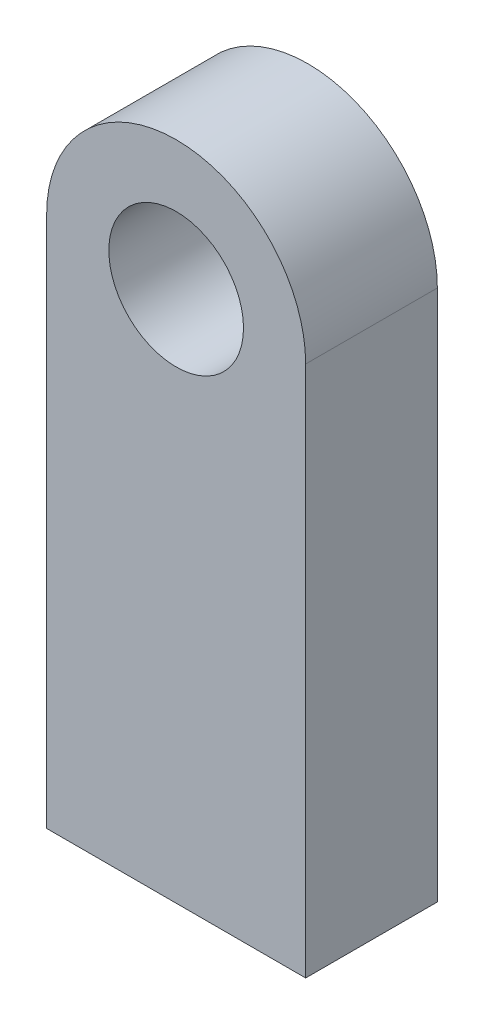
SolidWorks part; units mm, degrees
ref_plane "Front Plane" through (0, 0, 0) normal (0, 0, 1) x (1, 0, 0)
ref_plane "Top Plane" through (0, 0, 0) normal (0, 1, 0) x (1, 0, 0)
ref_plane "Right Plane" through (0, 0, 0) normal (1, 0, 0) x (0, 0, -1)
sketch "Sketch1" plane through (0, 0, 0) normal (0, 0, 1) x (1, 0, 0)
  line L0 (0, 0) -> (-19.6703, 0)
  line L1 (-19.6703, 0) -> (-19.6703, 40.3819)
  line L2 (0, 0) -> (0, 40.3819)
  arc A0 (-19.6703, 40.3819) -> (0, 40.3819) centre (-9.8351, 40.3819) cw
extrude "Boss-Extrude1" add sketch "Sketch1" along normal blind 10
sketch "Sketch2" plane through (0, 0, 10) normal (0, 0, 1) x (1, 0, 0)
  circle A0 centre (-9.8351, 40.3819) radius 5.1141
  arc A1 (0, 40.3819) -> (-19.6703, 40.3819) centre (-9.8351, 40.3819) ccw construction
extrude "Cut-Extrude1" cut sketch "Sketch2" against normal up to next
